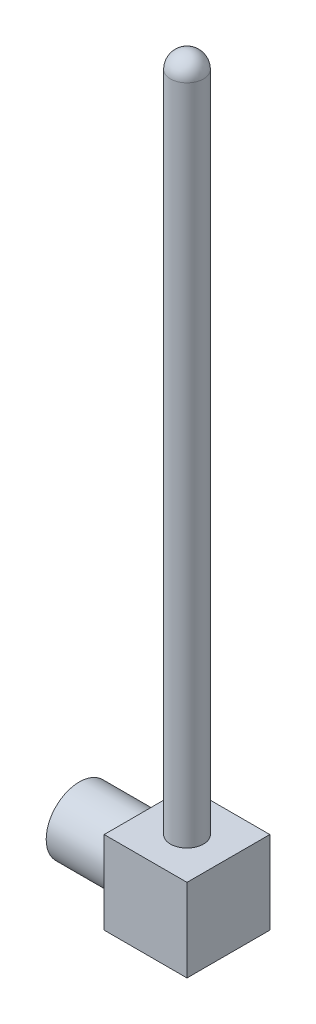
SolidWorks part; units mm, degrees
ref_plane "Front Plane" through (0, 0, 0) normal (0, 0, 1) x (1, 0, 0)
ref_plane "Top Plane" through (0, 0, 0) normal (0, 1, 0) x (1, 0, 0)
ref_plane "Right Plane" through (0, 0, 0) normal (1, 0, 0) x (0, 0, -1)
sketch "Sketch2" plane through (0, 0, 0) normal (0, 1, 0) x (1, 0, 0)
  circle A0 centre (0, 0) radius 5
  dimension "D1" = 10
extrude "Boss-Extrude1" add sketch "Sketch2" along normal blind 200
sketch "Sketch3" plane through (0, 0, 0) normal (0, -1, 0) x (1, 0, 0)
  line L1 (-12.5, 12.5) -> (12.5, 12.5)
  line L2 (-12.5, 12.5) -> (-12.5, -12.5)
  line L3 (-12.5, -12.5) -> (12.5, -12.5)
  line L4 (12.5, 12.5) -> (12.5, -12.5)
  line L5 (-12.5, 12.5) -> (12.5, -12.5) construction
  line L6 (-12.5, -12.5) -> (12.5, 12.5) construction
  point P0 (0, 0)
  dimension "D1" = 25
extrude "Boss-Extrude2" add sketch "Sketch3" along normal blind 25
sketch "Sketch4" plane through (-12.5, 0, 0) normal (-1, 0, 0) x (0, 0, 1)
  circle A0 centre (0, -12.5) radius 10
  dimension "D1" = 20
extrude "Boss-Extrude3" add sketch "Sketch4" along normal blind 20
sketch "Sketch6" plane through (0, 0, 0) normal (1, 0, 0) x (0, 0, -1)
  line L0 (-5, 200) -> (5, 200)
  line L1 (0, 198.0506) -> (0, 207.1942) construction
  arc A0 (-5, 200) -> (5, 200) centre (0, 200) cw
  dimension "D1" = 5
revolve "Revolve2" add sketch "Sketch6" angle 360 about L0
